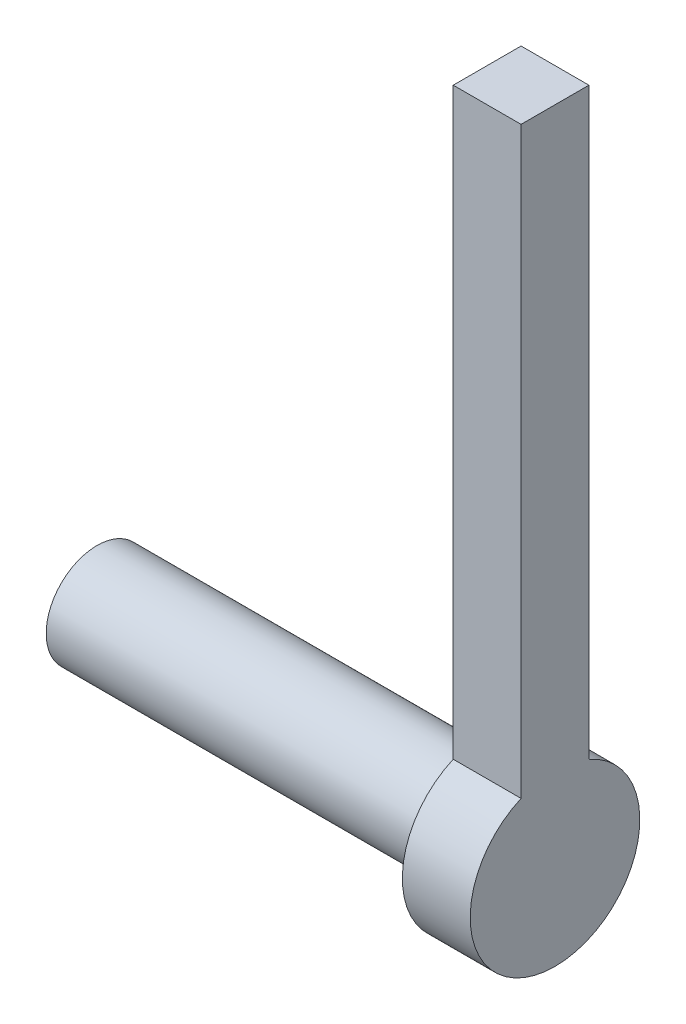
SolidWorks part; units mm, degrees
other "Preload Manual Lock Pin"
other "Preload Manual Lock Pin Left"
ref_plane "Front Plane" through (0, 0, 0) normal (0, 0, 1) x (1, 0, 0)
ref_plane "Top Plane" through (0, 0, 0) normal (0, 1, 0) x (1, 0, 0)
ref_plane "Right Plane" through (0, 0, 0) normal (1, 0, 0) x (0, 0, -1)
sketch3d "Service pin shank sketch datum points"
  point P0 (-12, -29, -10.5)
  point P1 (-12, -19, -10.5)
  point P2 (-12, -29, -0.5)
ref_plane "Service pin shank sketch plane" through (-12, 0, 0) normal (1, 0, 0) x (0, 0, -1)
sketch "Service pin shank sketch" plane through (-12, 0, 0) normal (1, 0, 0) x (0, 0, -1)
  circle A0 centre (10.5, -29) radius 1.5
extrude "Service pin shank" add sketch "Service pin shank sketch" along normal blind 11.5 separate body
sketch3d "Service pin head sketch datum points"
  point P0 (-0.5, -29, -10.5)
  point P1 (-0.5, -19, -10.5)
  point P2 (-0.5, -29, -0.5)
ref_plane "Service pin head sketch plane" through (-0.5, 0, 0) normal (1, 0, 0) x (0, 0, -1)
sketch "Service pin head sketch" plane through (-0.5, 0, 0) normal (1, 0, 0) x (0, 0, -1)
  circle A0 centre (10.5, -29) radius 2.5
extrude "Service pin head" add sketch "Service pin head sketch" along normal blind 2
sketch3d "Lock switch flag sketch datum points"
  point P0 (-0.5, -48.5, -11.5)
  point P1 (9.5, -48.5, -11.5)
  point P2 (-0.5, -38.5, -11.5)
ref_plane "Lock switch flag sketch plane" through (0, 0, -11.5) normal (0, 0, 1) x (1, 0, 0)
sketch "Lock switch flag sketch" plane through (0, 0, -11.5) normal (0, 0, 1) x (1, 0, 0)
  line L0 (-0.5, -48.5) -> (1.5, -48.5)
  line L1 (1.5, -48.5) -> (1.5, -29)
  line L2 (1.5, -29) -> (-0.5, -29)
  line L3 (-0.5, -29) -> (-0.5, -48.5)
extrude "Lock switch flag" add sketch "Lock switch flag sketch" along normal blind 2
sketch3d "Mirror1 profile datum points"
  point P0 (0, 0, 0)
  point P1 (10, 0, 0)
  point P2 (0, 0, 10)
ref_plane "Mirror1 profile plane" through (0, 0, 0) normal (0, -1, 0) x (-1, 0, 0)
mirror "Mirror1" about plane through (0, 0, 0) normal (0, -1, 0) of bodies 103
delete or keep bodies "Remove1" type delete bodies bodies 103
